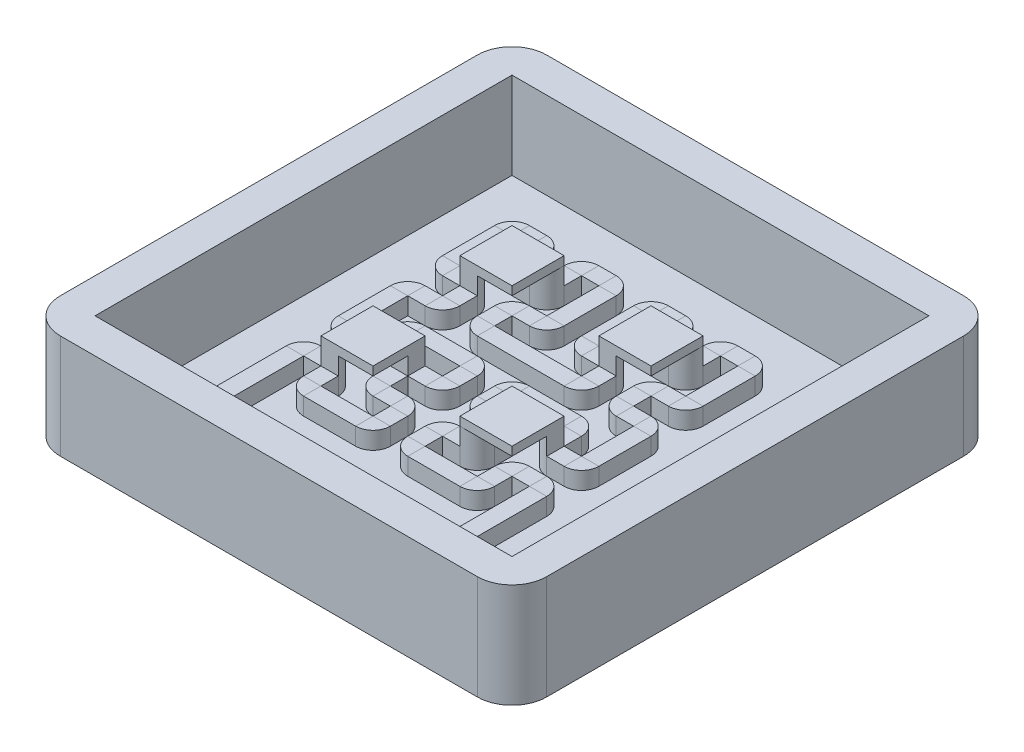
SolidWorks part; units mm, degrees
ref_plane "Front Plane" through (0, 0, 0) normal (0, 0, 1) x (1, 0, 0)
ref_plane "Top Plane" through (0, 0, 0) normal (0, 1, 0) x (1, 0, 0)
ref_plane "Right Plane" through (0, 0, 0) normal (1, 0, 0) x (0, 0, -1)
sketch "Sketch1" plane through (0, 0, 0) normal (0, 1, 0) x (1, 0, 0)
  line L0 (1, 1) -> (3, -1) construction
  line L1 (-1, -1) -> (1, -1)
  line L2 (-1, -1) -> (-1, 1)
  line L3 (-1, 1) -> (1, 1)
  line L4 (1, -1) -> (1, 1)
  line L5 (-1, -1) -> (1, 1) construction
  line L6 (-1, 1) -> (1, -1) construction
  line L7 (1, -1) -> (3, 1) construction
  line L8 (1, 1) -> (3, 1)
  line L9 (3, -1) -> (3, 1)
  line L10 (1, -1) -> (1, 1)
  line L11 (1, -1) -> (3, -1)
  line L12 (3, 1) -> (5, -1) construction
  line L13 (3, -1) -> (5, 1) construction
  line L14 (3, 1) -> (5, 1)
  line L15 (5, -1) -> (5, 1)
  line L16 (3, -1) -> (3, 1)
  line L17 (3, -1) -> (5, -1)
  line L18 (5, 1) -> (7, -1) construction
  line L19 (5, -1) -> (7, 1) construction
  line L20 (5, 1) -> (7, 1)
  line L21 (7, -1) -> (7, 1)
  line L22 (5, -1) -> (5, 1)
  line L23 (5, -1) -> (7, -1)
  line L24 (7, 1) -> (9, -1) construction
  line L25 (7, -1) -> (9, 1) construction
  line L26 (7, 1) -> (9, 1)
  line L27 (9, -1) -> (9, 1)
  line L28 (7, -1) -> (7, 1)
  line L29 (7, -1) -> (9, -1)
  line L30 (9, 1) -> (11, -1) construction
  line L31 (9, -1) -> (11, 1) construction
  line L32 (9, 1) -> (11, 1)
  line L33 (11, -1) -> (11, 1)
  line L34 (9, -1) -> (9, 1)
  line L35 (9, -1) -> (11, -1)
  line L36 (11, 1) -> (13, -1) construction
  line L37 (11, -1) -> (13, 1) construction
  line L38 (11, 1) -> (13, 1)
  line L39 (13, -1) -> (13, 1)
  line L40 (11, -1) -> (11, 1)
  line L41 (11, -1) -> (13, -1)
  line L42 (13, 1) -> (15, -1) construction
  line L43 (13, -1) -> (15, 1) construction
  line L44 (13, 1) -> (15, 1)
  line L45 (15, -1) -> (15, 1)
  line L46 (13, -1) -> (13, 1)
  line L47 (13, -1) -> (15, -1)
  line L96 (-1, 1) -> (1, 1)
  line L97 (-1, 1) -> (-1, 3)
  line L98 (-1, 3) -> (1, 3)
  line L99 (1, 1) -> (1, 3)
  line L100 (1, 3) -> (3, 3)
  line L101 (3, 1) -> (3, 3)
  line L102 (1, 1) -> (1, 3)
  line L103 (1, 1) -> (3, 1)
  line L104 (3, 3) -> (5, 3)
  line L105 (5, 1) -> (5, 3)
  line L106 (3, 1) -> (3, 3)
  line L107 (3, 1) -> (5, 1)
  line L108 (5, 3) -> (7, 3)
  line L109 (7, 1) -> (7, 3)
  line L110 (5, 1) -> (5, 3)
  line L111 (5, 1) -> (7, 1)
  line L112 (7, 3) -> (9, 3)
  line L113 (9, 1) -> (9, 3)
  line L114 (7, 1) -> (7, 3)
  line L115 (7, 1) -> (9, 1)
  line L116 (9, 3) -> (11, 3)
  line L117 (11, 1) -> (11, 3)
  line L118 (9, 1) -> (9, 3)
  line L119 (9, 1) -> (11, 1)
  line L120 (11, 3) -> (13, 3)
  line L121 (13, 1) -> (13, 3)
  line L122 (11, 1) -> (11, 3)
  line L123 (11, 1) -> (13, 1)
  line L124 (13, 3) -> (15, 3)
  line L125 (15, 1) -> (15, 3)
  line L126 (13, 1) -> (13, 3)
  line L127 (13, 1) -> (15, 1)
  line L160 (1, 3) -> (3, 1) construction
  line L161 (-1, 1) -> (1, 3) construction
  line L162 (-1, 3) -> (1, 1) construction
  line L163 (1, 1) -> (3, 3) construction
  line L164 (3, 3) -> (5, 1) construction
  line L165 (3, 1) -> (5, 3) construction
  line L166 (5, 3) -> (7, 1) construction
  line L167 (5, 1) -> (7, 3) construction
  line L168 (7, 3) -> (9, 1) construction
  line L169 (7, 1) -> (9, 3) construction
  line L170 (9, 3) -> (11, 1) construction
  line L171 (9, 1) -> (11, 3) construction
  line L172 (11, 3) -> (13, 1) construction
  line L173 (11, 1) -> (13, 3) construction
  line L174 (13, 3) -> (15, 1) construction
  line L175 (13, 1) -> (15, 3) construction
  line L192 (-1, 3) -> (1, 3)
  line L193 (-1, 3) -> (-1, 5)
  line L194 (-1, 5) -> (1, 5)
  line L195 (1, 3) -> (1, 5)
  line L196 (1, 5) -> (3, 5)
  line L197 (3, 3) -> (3, 5)
  line L198 (1, 3) -> (1, 5)
  line L199 (1, 3) -> (3, 3)
  line L200 (3, 5) -> (5, 5)
  line L201 (5, 3) -> (5, 5)
  line L202 (3, 3) -> (3, 5)
  line L203 (3, 3) -> (5, 3)
  line L204 (5, 5) -> (7, 5)
  line L205 (7, 3) -> (7, 5)
  line L206 (5, 3) -> (5, 5)
  line L207 (5, 3) -> (7, 3)
  line L208 (7, 5) -> (9, 5)
  line L209 (9, 3) -> (9, 5)
  line L210 (7, 3) -> (7, 5)
  line L211 (7, 3) -> (9, 3)
  line L212 (9, 5) -> (11, 5)
  line L213 (11, 3) -> (11, 5)
  line L214 (9, 3) -> (9, 5)
  line L215 (9, 3) -> (11, 3)
  line L216 (11, 5) -> (13, 5)
  line L217 (13, 3) -> (13, 5)
  line L218 (11, 3) -> (11, 5)
  line L219 (11, 3) -> (13, 3)
  line L220 (13, 5) -> (15, 5)
  line L221 (15, 3) -> (15, 5)
  line L222 (13, 3) -> (13, 5)
  line L223 (13, 3) -> (15, 3)
  line L256 (1, 5) -> (3, 3) construction
  line L257 (-1, 3) -> (1, 5) construction
  line L258 (-1, 5) -> (1, 3) construction
  line L259 (1, 3) -> (3, 5) construction
  line L260 (3, 5) -> (5, 3) construction
  line L261 (3, 3) -> (5, 5) construction
  line L262 (5, 5) -> (7, 3) construction
  line L263 (5, 3) -> (7, 5) construction
  line L264 (7, 5) -> (9, 3) construction
  line L265 (7, 3) -> (9, 5) construction
  line L266 (9, 5) -> (11, 3) construction
  line L267 (9, 3) -> (11, 5) construction
  line L268 (11, 5) -> (13, 3) construction
  line L269 (11, 3) -> (13, 5) construction
  line L270 (13, 5) -> (15, 3) construction
  line L271 (13, 3) -> (15, 5) construction
  line L288 (-1, 5) -> (1, 5)
  line L289 (-1, 5) -> (-1, 7)
  line L290 (-1, 7) -> (1, 7)
  line L291 (1, 5) -> (1, 7)
  line L292 (1, 7) -> (3, 7)
  line L293 (3, 5) -> (3, 7)
  line L294 (1, 5) -> (1, 7)
  line L295 (1, 5) -> (3, 5)
  line L296 (3, 7) -> (5, 7)
  line L297 (5, 5) -> (5, 7)
  line L298 (3, 5) -> (3, 7)
  line L299 (3, 5) -> (5, 5)
  line L300 (5, 7) -> (7, 7)
  line L301 (7, 5) -> (7, 7)
  line L302 (5, 5) -> (5, 7)
  line L303 (5, 5) -> (7, 5)
  line L304 (7, 7) -> (9, 7)
  line L305 (9, 5) -> (9, 7)
  line L306 (7, 5) -> (7, 7)
  line L307 (7, 5) -> (9, 5)
  line L308 (9, 7) -> (11, 7)
  line L309 (11, 5) -> (11, 7)
  line L310 (9, 5) -> (9, 7)
  line L311 (9, 5) -> (11, 5)
  line L312 (11, 7) -> (13, 7)
  line L313 (13, 5) -> (13, 7)
  line L314 (11, 5) -> (11, 7)
  line L315 (11, 5) -> (13, 5)
  line L316 (13, 7) -> (15, 7)
  line L317 (15, 5) -> (15, 7)
  line L318 (13, 5) -> (13, 7)
  line L319 (13, 5) -> (15, 5)
  line L352 (1, 7) -> (3, 5) construction
  line L353 (-1, 5) -> (1, 7) construction
  line L354 (-1, 7) -> (1, 5) construction
  line L355 (1, 5) -> (3, 7) construction
  line L356 (3, 7) -> (5, 5) construction
  line L357 (3, 5) -> (5, 7) construction
  line L358 (5, 7) -> (7, 5) construction
  line L359 (5, 5) -> (7, 7) construction
  line L360 (7, 7) -> (9, 5) construction
  line L361 (7, 5) -> (9, 7) construction
  line L362 (9, 7) -> (11, 5) construction
  line L363 (9, 5) -> (11, 7) construction
  line L364 (11, 7) -> (13, 5) construction
  line L365 (11, 5) -> (13, 7) construction
  line L366 (13, 7) -> (15, 5) construction
  line L367 (13, 5) -> (15, 7) construction
  line L384 (-1, 7) -> (1, 7)
  line L385 (-1, 7) -> (-1, 9)
  line L386 (-1, 9) -> (1, 9)
  line L387 (1, 7) -> (1, 9)
  line L388 (1, 9) -> (3, 9)
  line L389 (3, 7) -> (3, 9)
  line L390 (1, 7) -> (1, 9)
  line L391 (1, 7) -> (3, 7)
  line L392 (3, 9) -> (5, 9)
  line L393 (5, 7) -> (5, 9)
  line L394 (3, 7) -> (3, 9)
  line L395 (3, 7) -> (5, 7)
  line L396 (5, 9) -> (7, 9)
  line L397 (7, 7) -> (7, 9)
  line L398 (5, 7) -> (5, 9)
  line L399 (5, 7) -> (7, 7)
  line L400 (7, 9) -> (9, 9)
  line L401 (9, 7) -> (9, 9)
  line L402 (7, 7) -> (7, 9)
  line L403 (7, 7) -> (9, 7)
  line L404 (9, 9) -> (11, 9)
  line L405 (11, 7) -> (11, 9)
  line L406 (9, 7) -> (9, 9)
  line L407 (9, 7) -> (11, 7)
  line L408 (11, 9) -> (13, 9)
  line L409 (13, 7) -> (13, 9)
  line L410 (11, 7) -> (11, 9)
  line L411 (11, 7) -> (13, 7)
  line L412 (13, 9) -> (15, 9)
  line L413 (15, 7) -> (15, 9)
  line L414 (13, 7) -> (13, 9)
  line L415 (13, 7) -> (15, 7)
  line L448 (1, 9) -> (3, 7) construction
  line L449 (-1, 7) -> (1, 9) construction
  line L450 (-1, 9) -> (1, 7) construction
  line L451 (1, 7) -> (3, 9) construction
  line L452 (3, 9) -> (5, 7) construction
  line L453 (3, 7) -> (5, 9) construction
  line L454 (5, 9) -> (7, 7) construction
  line L455 (5, 7) -> (7, 9) construction
  line L456 (7, 9) -> (9, 7) construction
  line L457 (7, 7) -> (9, 9) construction
  line L458 (9, 9) -> (11, 7) construction
  line L459 (9, 7) -> (11, 9) construction
  line L460 (11, 9) -> (13, 7) construction
  line L461 (11, 7) -> (13, 9) construction
  line L462 (13, 9) -> (15, 7) construction
  line L463 (13, 7) -> (15, 9) construction
  line L480 (-1, 9) -> (1, 9)
  line L481 (-1, 9) -> (-1, 11)
  line L482 (-1, 11) -> (1, 11)
  line L483 (1, 9) -> (1, 11)
  line L484 (1, 11) -> (3, 11)
  line L485 (3, 9) -> (3, 11)
  line L486 (1, 9) -> (1, 11)
  line L487 (1, 9) -> (3, 9)
  line L488 (3, 11) -> (5, 11)
  line L489 (5, 9) -> (5, 11)
  line L490 (3, 9) -> (3, 11)
  line L491 (3, 9) -> (5, 9)
  line L492 (5, 11) -> (7, 11)
  line L493 (7, 9) -> (7, 11)
  line L494 (5, 9) -> (5, 11)
  line L495 (5, 9) -> (7, 9)
  line L496 (7, 11) -> (9, 11)
  line L497 (9, 9) -> (9, 11)
  line L498 (7, 9) -> (7, 11)
  line L499 (7, 9) -> (9, 9)
  line L500 (9, 11) -> (11, 11)
  line L501 (11, 9) -> (11, 11)
  line L502 (9, 9) -> (9, 11)
  line L503 (9, 9) -> (11, 9)
  line L504 (11, 11) -> (13, 11)
  line L505 (13, 9) -> (13, 11)
  line L506 (11, 9) -> (11, 11)
  line L507 (11, 9) -> (13, 9)
  line L508 (13, 11) -> (15, 11)
  line L509 (15, 9) -> (15, 11)
  line L510 (13, 9) -> (13, 11)
  line L511 (13, 9) -> (15, 9)
  line L544 (1, 11) -> (3, 9) construction
  line L545 (-1, 9) -> (1, 11) construction
  line L546 (-1, 11) -> (1, 9) construction
  line L547 (1, 9) -> (3, 11) construction
  line L548 (3, 11) -> (5, 9) construction
  line L549 (3, 9) -> (5, 11) construction
  line L550 (5, 11) -> (7, 9) construction
  line L551 (5, 9) -> (7, 11) construction
  line L552 (7, 11) -> (9, 9) construction
  line L553 (7, 9) -> (9, 11) construction
  line L554 (9, 11) -> (11, 9) construction
  line L555 (9, 9) -> (11, 11) construction
  line L556 (11, 11) -> (13, 9) construction
  line L557 (11, 9) -> (13, 11) construction
  line L558 (13, 11) -> (15, 9) construction
  line L559 (13, 9) -> (15, 11) construction
  line L576 (-1, 11) -> (1, 11)
  line L577 (-1, 11) -> (-1, 13)
  line L578 (-1, 13) -> (1, 13)
  line L579 (1, 11) -> (1, 13)
  line L580 (1, 13) -> (3, 13)
  line L581 (3, 11) -> (3, 13)
  line L582 (1, 11) -> (1, 13)
  line L583 (1, 11) -> (3, 11)
  line L584 (3, 13) -> (5, 13)
  line L585 (5, 11) -> (5, 13)
  line L586 (3, 11) -> (3, 13)
  line L587 (3, 11) -> (5, 11)
  line L588 (5, 13) -> (7, 13)
  line L589 (7, 11) -> (7, 13)
  line L590 (5, 11) -> (5, 13)
  line L591 (5, 11) -> (7, 11)
  line L592 (7, 13) -> (9, 13)
  line L593 (9, 11) -> (9, 13)
  line L594 (7, 11) -> (7, 13)
  line L595 (7, 11) -> (9, 11)
  line L596 (9, 13) -> (11, 13)
  line L597 (11, 11) -> (11, 13)
  line L598 (9, 11) -> (9, 13)
  line L599 (9, 11) -> (11, 11)
  line L600 (11, 13) -> (13, 13)
  line L601 (13, 11) -> (13, 13)
  line L602 (11, 11) -> (11, 13)
  line L603 (11, 11) -> (13, 11)
  line L604 (13, 13) -> (15, 13)
  line L605 (15, 11) -> (15, 13)
  line L606 (13, 11) -> (13, 13)
  line L607 (13, 11) -> (15, 11)
  line L640 (1, 13) -> (3, 11) construction
  line L641 (-1, 11) -> (1, 13) construction
  line L642 (-1, 13) -> (1, 11) construction
  line L643 (1, 11) -> (3, 13) construction
  line L644 (3, 13) -> (5, 11) construction
  line L645 (3, 11) -> (5, 13) construction
  line L646 (5, 13) -> (7, 11) construction
  line L647 (5, 11) -> (7, 13) construction
  line L648 (7, 13) -> (9, 11) construction
  line L649 (7, 11) -> (9, 13) construction
  line L650 (9, 13) -> (11, 11) construction
  line L651 (9, 11) -> (11, 13) construction
  line L652 (11, 13) -> (13, 11) construction
  line L653 (11, 11) -> (13, 13) construction
  line L654 (13, 13) -> (15, 11) construction
  line L655 (13, 11) -> (15, 13) construction
  line L672 (-1, 13) -> (1, 13)
  line L673 (-1, 13) -> (-1, 15)
  line L674 (-1, 15) -> (1, 15)
  line L675 (1, 13) -> (1, 15)
  line L676 (1, 15) -> (3, 15)
  line L677 (3, 13) -> (3, 15)
  line L678 (1, 13) -> (1, 15)
  line L679 (1, 13) -> (3, 13)
  line L680 (3, 15) -> (5, 15)
  line L681 (5, 13) -> (5, 15)
  line L682 (3, 13) -> (3, 15)
  line L683 (3, 13) -> (5, 13)
  line L684 (5, 15) -> (7, 15)
  line L685 (7, 13) -> (7, 15)
  line L686 (5, 13) -> (5, 15)
  line L687 (5, 13) -> (7, 13)
  line L688 (7, 15) -> (9, 15)
  line L689 (9, 13) -> (9, 15)
  line L690 (7, 13) -> (7, 15)
  line L691 (7, 13) -> (9, 13)
  line L692 (9, 15) -> (11, 15)
  line L693 (11, 13) -> (11, 15)
  line L694 (9, 13) -> (9, 15)
  line L695 (9, 13) -> (11, 13)
  line L696 (11, 15) -> (13, 15)
  line L697 (13, 13) -> (13, 15)
  line L698 (11, 13) -> (11, 15)
  line L699 (11, 13) -> (13, 13)
  line L700 (13, 15) -> (15, 15)
  line L701 (15, 13) -> (15, 15)
  line L702 (13, 13) -> (13, 15)
  line L703 (13, 13) -> (15, 13)
  line L736 (1, 15) -> (3, 13) construction
  line L737 (-1, 13) -> (1, 15) construction
  line L738 (-1, 15) -> (1, 13) construction
  line L739 (1, 13) -> (3, 15) construction
  line L740 (3, 15) -> (5, 13) construction
  line L741 (3, 13) -> (5, 15) construction
  line L742 (5, 15) -> (7, 13) construction
  line L743 (5, 13) -> (7, 15) construction
  line L744 (7, 15) -> (9, 13) construction
  line L745 (7, 13) -> (9, 15) construction
  line L746 (9, 15) -> (11, 13) construction
  line L747 (9, 13) -> (11, 15) construction
  line L748 (11, 15) -> (13, 13) construction
  line L749 (11, 13) -> (13, 15) construction
  line L750 (13, 15) -> (15, 13) construction
  line L751 (13, 13) -> (15, 15) construction
  point P0 (0, 0)
  point P7 (2, 0)
  point P69 (0, 2)
  point P134 (0, 4)
  point P199 (0, 6)
  point P264 (0, 8)
  point P329 (0, 10)
  point P394 (0, 12)
  point P459 (0, 14)
  dimension "D1" = 2
  dimension "D3" = 2
  dimension "D5" = 2
  dimension "D2" = 8
  dimension "D4" = 8
sketch "Sketch2" plane through (0, 0, 0) normal (0, 1, 0) x (1, 0, 0)
  line L0 (0, 0) -> (0, 1.5)
  line L1 (0.5, 2) -> (1.5, 2)
  line L2 (0, 0) -> (0, 14) construction
  line L3 (1, 3) -> (3, 1) construction
  line L4 (2, 1.5) -> (2, 0.5)
  line L6 (1, 1) -> (3, -1) construction
  line L7 (2.5, 0) -> (5.5, 0)
  line L8 (5, 1) -> (7, -1) construction
  line L9 (6, 0.5) -> (6, 1.5)
  line L10 (5, 1) -> (7, 3) construction
  line L11 (5.5, 2) -> (4.5, 2)
  line L13 (3, 3) -> (5, 1) construction
  line L14 (4, 2.5) -> (4, 3.5)
  line L15 (3, 5) -> (5, 3) construction
  line L17 (4.5, 4) -> (5.5, 4)
  line L18 (5, 5) -> (7, 3) construction
  line L19 (6, 4.5) -> (6, 5.5)
  line L21 (5, 7) -> (7, 5) construction
  line L22 (5.5, 6) -> (2.5, 6)
  line L23 (1, 7) -> (3, 5) construction
  line L25 (2, 5.5) -> (2, 4.5)
  line L26 (1, 5) -> (3, 3) construction
  line L27 (1.5, 4) -> (0.5, 4)
  line L29 (0, 4.5) -> (0, 7.5)
  line L30 (0.5, 8) -> (1.5, 8)
  line L31 (1, 9) -> (3, 7) construction
  line L33 (2, 8.5) -> (2, 9.5)
  line L34 (1, 11) -> (3, 9) construction
  line L35 (1.5, 10) -> (0.5, 10)
  line L37 (0, 10.5) -> (0, 13.5)
  line L38 (0.5, 14) -> (1.5, 14)
  line L39 (1, 15) -> (3, 13) construction
  line L41 (2, 13.5) -> (2, 12.5)
  line L42 (1, 13) -> (3, 11) construction
  line L43 (2.5, 12) -> (3.5, 12)
  line L45 (3, 13) -> (5, 11) construction
  line L46 (4, 12.5) -> (4, 13.5)
  line L47 (3, 15) -> (5, 13) construction
  line L49 (4.5, 14) -> (5.5, 14)
  line L50 (5, 13) -> (7, 15) construction
  line L51 (6, 13.5) -> (6, 10.5)
  line L53 (5, 11) -> (7, 9) construction
  line L54 (5.5, 10) -> (4.5, 10)
  line L55 (3, 11) -> (5, 9) construction
  line L57 (4, 9.5) -> (4, 8.5)
  line L58 (3, 9) -> (5, 7) construction
  line L59 (4.5, 8) -> (9.5, 8)
  line L61 (9, 7) -> (11, 9) construction
  line L62 (10, 8.5) -> (10, 9.5)
  line L63 (9, 9) -> (11, 11) construction
  line L65 (9.5, 10) -> (8.5, 10)
  line L66 (7, 11) -> (9, 9) construction
  line L67 (8, 10.5) -> (8, 13.5)
  line L69 (7, 15) -> (9, 13) construction
  line L70 (8.5, 14) -> (9.5, 14)
  line L71 (9, 15) -> (11, 13) construction
  line L73 (10, 13.5) -> (10, 12.5)
  line L74 (9, 11) -> (11, 13) construction
  line L75 (10.5, 12) -> (11.5, 12)
  line L77 (11, 13) -> (13, 11) construction
  line L78 (12, 12.5) -> (12, 13.5)
  line L79 (11, 15) -> (13, 13) construction
  line L81 (12.5, 14) -> (13.5, 14)
  line L82 (13, 15) -> (15, 13) construction
  line L83 (14, 13.5) -> (14, 10.5)
  line L85 (13, 11) -> (15, 9) construction
  line L86 (13.5, 10) -> (12.5, 10)
  line L87 (11, 11) -> (13, 9) construction
  line L89 (12, 9.5) -> (12, 8.5)
  line L90 (11, 9) -> (13, 7) construction
  line L92 (12.5, 8) -> (13.5, 8)
  line L93 (13, 9) -> (15, 7) construction
  line L94 (14, 7.5) -> (14, 4.5)
  line L96 (13, 5) -> (15, 3) construction
  line L97 (13.5, 4) -> (12.5, 4)
  line L99 (11, 5) -> (13, 3) construction
  line L100 (12, 4.5) -> (12, 5.5)
  line L102 (11, 7) -> (13, 5) construction
  line L103 (11.5, 6) -> (8.5, 6)
  line L104 (7, 7) -> (9, 5) construction
  line L106 (8, 5.5) -> (8, 4.5)
  line L107 (7, 5) -> (9, 3) construction
  line L108 (8.5, 4) -> (9.5, 4)
  line L110 (9, 5) -> (11, 3) construction
  line L111 (10, 3.5) -> (10, 2.5)
  line L112 (9, 3) -> (11, 1) construction
  line L114 (9.5, 2) -> (8.5, 2)
  line L115 (7, 3) -> (9, 1) construction
  line L116 (8, 1.5) -> (8, 0.5)
  line L118 (7, 1) -> (9, -1) construction
  line L119 (8.5, 0) -> (11.5, 0)
  line L121 (11, 1) -> (13, -1) construction
  line L122 (12, 0.5) -> (12, 1.5)
  line L124 (11, 3) -> (13, 1) construction
  line L125 (12.5, 2) -> (13.5, 2)
  line L127 (13, 1) -> (15, 3) construction
  line L128 (14, 1.5) -> (14, 0)
  line L130 (13, 1) -> (15, -1) construction
  arc A0 (14, 1.5) -> (13.5, 2) centre (13.5, 1.5) ccw
  arc A1 (12.5, 2) -> (12, 1.5) centre (12.5, 1.5) ccw
  arc A2 (12, 0.5) -> (11.5, 0) centre (11.5, 0.5) cw
  arc A3 (8.5, 0) -> (8, 0.5) centre (8.5, 0.5) cw
  arc A4 (8, 1.5) -> (8.5, 2) centre (8.5, 1.5) cw
  arc A5 (9.5, 2) -> (10, 2.5) centre (9.5, 2.5) ccw
  arc A6 (10, 3.5) -> (9.5, 4) centre (9.5, 3.5) ccw
  arc A7 (8.5, 4) -> (8, 4.5) centre (8.5, 4.5) cw
  arc A8 (8, 5.5) -> (8.5, 6) centre (8.5, 5.5) cw
  arc A9 (11.5, 6) -> (12, 5.5) centre (11.5, 5.5) cw
  arc A10 (12, 4.5) -> (12.5, 4) centre (12.5, 4.5) ccw
  arc A11 (13.5, 4) -> (14, 4.5) centre (13.5, 4.5) ccw
  arc A12 (14, 7.5) -> (13.5, 8) centre (13.5, 7.5) ccw
  arc A13 (12.5, 8) -> (12, 8.5) centre (12.5, 8.5) cw
  arc A14 (12, 9.5) -> (12.5, 10) centre (12.5, 9.5) cw
  arc A15 (13.5, 10) -> (14, 10.5) centre (13.5, 10.5) ccw
  arc A16 (14, 13.5) -> (13.5, 14) centre (13.5, 13.5) ccw
  arc A17 (12.5, 14) -> (12, 13.5) centre (12.5, 13.5) ccw
  arc A18 (12, 12.5) -> (11.5, 12) centre (11.5, 12.5) cw
  arc A19 (10.5, 12) -> (10, 12.5) centre (10.5, 12.5) cw
  arc A20 (10, 13.5) -> (9.5, 14) centre (9.5, 13.5) ccw
  arc A21 (8.5, 14) -> (8, 13.5) centre (8.5, 13.5) ccw
  arc A22 (8, 10.5) -> (8.5, 10) centre (8.5, 10.5) ccw
  arc A23 (9.5, 10) -> (10, 9.5) centre (9.5, 9.5) cw
  arc A24 (10, 8.5) -> (9.5, 8) centre (9.5, 8.5) cw
  arc A25 (4.5, 8) -> (4, 8.5) centre (4.5, 8.5) cw
  arc A26 (4, 9.5) -> (4.5, 10) centre (4.5, 9.5) cw
  arc A27 (5.5, 10) -> (6, 10.5) centre (5.5, 10.5) ccw
  arc A28 (6, 13.5) -> (5.5, 14) centre (5.5, 13.5) ccw
  arc A29 (4.5, 14) -> (4, 13.5) centre (4.5, 13.5) ccw
  arc A30 (4, 12.5) -> (3.5, 12) centre (3.5, 12.5) cw
  arc A31 (2.5, 12) -> (2, 12.5) centre (2.5, 12.5) cw
  arc A32 (2, 13.5) -> (1.5, 14) centre (1.5, 13.5) ccw
  arc A33 (0.5, 14) -> (0, 13.5) centre (0.5, 13.5) ccw
  arc A34 (0, 10.5) -> (0.5, 10) centre (0.5, 10.5) ccw
  arc A35 (1.5, 10) -> (2, 9.5) centre (1.5, 9.5) cw
  arc A36 (2, 8.5) -> (1.5, 8) centre (1.5, 8.5) cw
  arc A37 (0.5, 8) -> (0, 7.5) centre (0.5, 7.5) ccw
  arc A38 (0, 4.5) -> (0.5, 4) centre (0.5, 4.5) ccw
  arc A39 (2, 4.5) -> (1.5, 4) centre (1.5, 4.5) cw
  arc A40 (2, 5.5) -> (2.5, 6) centre (2.5, 5.5) cw
  arc A41 (5.5, 6) -> (6, 5.5) centre (5.5, 5.5) cw
  arc A42 (6, 4.5) -> (5.5, 4) centre (5.5, 4.5) cw
  arc A43 (4.5, 4) -> (4, 3.5) centre (4.5, 3.5) ccw
  arc A44 (4, 2.5) -> (4.5, 2) centre (4.5, 2.5) ccw
  arc A45 (5.5, 2) -> (6, 1.5) centre (5.5, 1.5) cw
  arc A46 (6, 0.5) -> (5.5, 0) centre (5.5, 0.5) cw
  arc A47 (2.5, 0) -> (2, 0.5) centre (2.5, 0.5) cw
  arc A48 (2, 1.5) -> (1.5, 2) centre (1.5, 1.5) ccw
  arc A49 (0.5, 2) -> (0, 1.5) centre (0.5, 1.5) ccw
  point P146 (14, 2)
  point P149 (12, 2)
  point P152 (12, 0)
  point P155 (8, 0)
  point P158 (8, 2)
  point P161 (10, 2)
  point P164 (10, 4)
  point P167 (8, 4)
  point P170 (8, 6)
  point P173 (12, 6)
  point P176 (12, 4)
  point P179 (14, 4)
  point P182 (14, 8)
  point P185 (12, 8)
  point P188 (12, 10)
  point P191 (14, 10)
  point P194 (14, 14)
  point P197 (12, 14)
  point P200 (12, 12)
  point P203 (10, 12)
  point P206 (10, 14)
  point P209 (8, 14)
  point P212 (8, 10)
  point P215 (10, 10)
  point P218 (10, 8)
  point P221 (4, 8)
  point P224 (4, 10)
  point P227 (6, 10)
  point P230 (6, 14)
  point P233 (4, 14)
  point P236 (4, 12)
  point P239 (2, 12)
  point P242 (2, 14)
  point P245 (0, 14)
  point P248 (0, 10)
  point P251 (2, 10)
  point P254 (2, 8)
  point P257 (0, 8)
  point P260 (0, 4)
  point P263 (2, 4)
  point P266 (2, 6)
  point P269 (6, 6)
  point P272 (6, 4)
  point P275 (4, 4)
  point P278 (4, 2)
  point P281 (6, 2)
  point P284 (6, 0)
  point P287 (2, 0)
  point P290 (2, 2)
  point P293 (0, 2)
  dimension "D1" = 0.5
ref_plane "Plane1" through (0, 0, 0) normal (0, 0, 1) x (1, 0, 0)
sketch "Sketch3" plane through (0, 0, 0) normal (0, 0, 1) x (1, 0, 0)
  line L6 (-0.5, -0.5) -> (0.5, -0.5)
  line L7 (-0.5, -0.5) -> (-0.5, 0.5)
  line L8 (-0.5, 0.5) -> (0.5, 0.5)
  line L9 (0.5, -0.5) -> (0.5, 0.5)
  line L10 (-0.5, -0.5) -> (0.5, 0.5) construction
  line L11 (-0.5, 0.5) -> (0.5, -0.5) construction
  point P1 (0, 0)
  dimension "D2" = 1
sweep "Sweep1" add profiles "Sketch3" path "Sketch2"
sketch "Sketch4" plane through (0, 0, 0) normal (0, 0, 1) x (1, 0, 0)
  line L1 (-0.5, -0.5) -> (0.5, -0.5)
  line L2 (-0.5, -0.5) -> (-0.5, 0.5)
  line L3 (-0.5, 0.5) -> (0.5, 0.5)
  line L4 (0.5, -0.5) -> (0.5, 0.5)
  line L5 (-0.5, -0.5) -> (0.5, 0.5) construction
  line L6 (-0.5, 0.5) -> (0.5, -0.5) construction
  line L7 (13.5, 0.5) -> (14.5, 0.5)
  line L8 (13.5, 0.5) -> (13.5, -0.5)
  line L9 (13.5, -0.5) -> (14.5, -0.5)
  line L10 (14.5, 0.5) -> (14.5, -0.5)
  point P0 (0, 0)
extrude "Boss-Extrude1" add sketch "Sketch4" along normal blind 5
ref_plane "Plane2" through (0, -2, 0) normal (0, 1, 0) x (1, 0, 0)
sketch "Sketch7" plane through (0, -2, 0) normal (0, 1, 0) x (1, 0, 0)
  line L0 (5.5, 14.5) -> (5.5, -0.5) construction
  line L6 (14.5, -5) -> (13.5, -5) construction
  line L7 (-5, -5) -> (19, -5)
  line L8 (5.5, -0.5) -> (8.5, -0.5) construction
  line L9 (-5, -5) -> (-5, 19)
  line L10 (-5, 19) -> (19, 19)
  line L11 (8.5, -0.5) -> (8.5, 14.5) construction
  line L12 (8.5, 7) -> (5.5, 7) construction
  line L18 (2.5, -0.5) -> (5.5, -0.5) construction
  line L19 (5.5, -0.5) -> (5.5, 0.5) construction
  line L20 (19, -5) -> (19, 19)
  line L21 (-5, -5) -> (19, 19) construction
  line L22 (-5, 19) -> (19, -5) construction
  point P7 (7, 7)
  point P10 (7, 7)
extrude "Boss-Extrude4" add sketch "Sketch7" against normal blind 1 separate body
sketch "Sketch8" plane through (0, -3, 0) normal (0, -1, 0) x (1, 0, 0)
  line L0 (-5, -19) -> (-5, 5) construction
  line L1 (-7, 7) -> (21, 7)
  line L2 (-7, 7) -> (-7, -21)
  line L3 (-7, -21) -> (21, -21)
  line L4 (21, 7) -> (21, -21)
  line L5 (19, 5) -> (19, -19) construction
  line L8 (-5, 5) -> (19, 5)
  line L9 (-5, 5) -> (-5, -19)
  line L10 (-5, -19) -> (19, -19)
  line L11 (19, 5) -> (19, -19)
  dimension "D1" = 2
  dimension "D2" = 2
  dimension "D3" = 2
extrude "Boss-Extrude5" add sketch "Sketch8" against normal blind 5
fillet "Fillet1" radius 2 4 edges at (-7, -0.5, 7) (21, -0.5, 7) (21, -0.5, -21) (-7, -0.5, -21)
sketch "Sketch10" plane through (0, 0, -14.5) normal (0, 0, -1) x (-1, 0, 0)
  line L0 (-1, 0.5) -> (-1, -0.5) construction
  line L1 (-0.5, 0.5) -> (-1.5, 0.5) construction
  line L2 (-0.5, -0.5) -> (-1.5, -0.5) construction
  line L3 (-13, 0.5) -> (-13, -0.5) construction
  line L4 (-12.5, 0.5) -> (-13.5, 0.5) construction
  line L5 (-12.5, -0.5) -> (-13.5, -0.5) construction
  circle A0 centre (-13, 0) radius 0.35
  circle A1 centre (-1, 0) radius 0.35
  dimension "D1" = 0.7
  dimension "D2" = 0.7
extrude "Boss-Extrude7" [suppressed] add sketch "Sketch10" along normal up to surface (4.5 mm away)
sketch "Sketch17" plane through (0, 0.5, 0) normal (0, 1, 0) x (1, 0, 0)
  line L0 (1.5, 9.5) -> (1.5, 10.5)
  line L1 (1.5, 10.5) -> (1.5, 9.5)
  line L2 (1.5, 9.5) -> (2.5, 9.5)
  line L3 (2.5, 8.5) -> (2.5, 9.5) construction
  line L4 (1.5, 9.5) -> (2.5, 9.5)
  line L5 (3.5, 12.5) -> (4.5, 12.5)
  line L6 (3.5, 12.5) -> (3.5, 11.5)
  line L7 (1.5, 1.5) -> (1.5, 2.5)
  line L8 (1.5, 1.5) -> (2.5, 1.5)
  line L9 (3.5, 3.5) -> (4.5, 3.5)
  line L10 (4.5, 3.5) -> (4.5, 4.5)
  line L11 (9.5, 10.5) -> (9.5, 9.5)
  line L12 (9.5, 9.5) -> (10.5, 9.5)
  line L13 (10.5, 9.5) -> (9.5, 9.5) construction
  line L14 (11.5, 11.5) -> (11.5, 12.5)
  line L15 (11.5, 11.5) -> (11.5, 12.5) construction
  line L16 (11.5, 12.5) -> (12.5, 12.5)
  line L17 (11.5, 4.5) -> (12.5, 4.5)
  line L18 (12.5, 4.5) -> (12.5, 3.5)
  line L19 (10.5, 2.5) -> (9.5, 2.5)
  line L20 (9.5, 2.5) -> (9.5, 1.5)
  line L21 (9.5, 1.5) -> (8.5, 1.5) construction
  arc A0 (1.5, 10.5) -> (2.5, 9.5) centre (1.5, 9.5) cw
  arc A1 (4.5, 12.5) -> (3.5, 11.5) centre (3.5, 12.5) cw
  arc A2 (1.5, 2.5) -> (2.5, 1.5) centre (1.5, 1.5) cw
  arc A3 (2.5, 1.5) -> (1.5, 2.5) centre (1.5, 1.5) ccw construction
  arc A4 (3.5, 3.5) -> (4.5, 4.5) centre (4.5, 3.5) cw
  arc A5 (10.5, 9.5) -> (9.5, 10.5) centre (9.5, 9.5) ccw construction
  arc A6 (9.5, 10.5) -> (10.5, 9.5) centre (9.5, 9.5) cw
  arc A7 (11.5, 11.5) -> (12.5, 12.5) centre (11.5, 12.5) ccw construction
  arc A8 (12.5, 12.5) -> (11.5, 11.5) centre (11.5, 12.5) cw
  arc A9 (11.5, 4.5) -> (12.5, 3.5) centre (12.5, 4.5) ccw
  arc A10 (11.5, 4.5) -> (12.5, 3.5) centre (12.5, 4.5) ccw construction
  arc A11 (10.5, 2.5) -> (9.5, 1.5) centre (9.5, 2.5) cw
  arc A12 (1.5, 10.5) -> (2.5, 9.5) centre (1.5, 9.5) cw
extrude "Boss-Extrude11" add sketch "Sketch17" along normal blind 1 contours A4 L9 L10 | A2 L7 L8 | A1 L5 L6 | A6 L11 L12 | A8 L16 L14 | L17 A9 L18 | A11 L19 L20
sketch "Sketch16" plane through (0, 2, 0) normal (0, 1, 0) x (1, 0, 0)
  line L1 (-5, 19) -> (19, 19)
  line L2 (-5, 19) -> (-5, -5)
  line L3 (-5, -5) -> (19, -5)
  line L4 (-7, 19) -> (-7, -5)
  line L5 (-5, -7) -> (19, -7)
  line L6 (21, -5) -> (21, 19)
  line L7 (19, 21) -> (-5, 21)
  line L8 (-7, 19) -> (-7, -5)
  line L9 (-5, -7) -> (19, -7)
  line L10 (21, -5) -> (21, 19)
  line L11 (19, 21) -> (-5, 21)
  line L12 (19, 19) -> (19, -5)
  arc A4 (-7, -5) -> (-5, -7) centre (-5, -5) ccw
  arc A5 (19, -7) -> (21, -5) centre (19, -5) ccw
  arc A6 (21, 19) -> (19, 21) centre (19, 19) ccw
  arc A7 (-5, 21) -> (-7, 19) centre (-5, 19) ccw
  arc A8 (-7, -5) -> (-5, -7) centre (-5, -5) ccw
  arc A9 (19, -7) -> (21, -5) centre (19, -5) ccw
  arc A10 (21, 19) -> (19, 21) centre (19, 19) ccw
  arc A11 (-5, 21) -> (-7, 19) centre (-5, 19) ccw
  dimension "D1" = 0
extrude "Boss-Extrude10" add sketch "Sketch16" along normal blind 1
sketch "Sketch18" plane through (0, 1.5, 0) normal (0, 1, 0) x (1, 0, 0)
  line L1 (9.5, 9.5) -> (12.5, 9.5)
  line L2 (9.5, 9.5) -> (9.5, 12.5)
  line L3 (9.5, 12.5) -> (12.5, 12.5)
  line L4 (12.5, 9.5) -> (12.5, 12.5)
  line L5 (1.5, 9.5) -> (4.5, 9.5)
  line L6 (1.5, 9.5) -> (1.5, 12.5)
  line L7 (1.5, 12.5) -> (4.5, 12.5)
  line L8 (4.5, 9.5) -> (4.5, 12.5)
  line L13 (1.5, 1.5) -> (4.5, 1.5)
  line L14 (1.5, 1.5) -> (1.5, 4.5)
  line L15 (1.5, 4.5) -> (4.5, 4.5)
  line L16 (4.5, 1.5) -> (4.5, 4.5)
  line L17 (9.5, 1.5) -> (12.5, 1.5)
  line L18 (9.5, 1.5) -> (9.5, 4.5)
  line L19 (9.5, 4.5) -> (12.5, 4.5)
  line L20 (12.5, 1.5) -> (12.5, 4.5)
  arc A0 (4.5, 4.5) -> (3.5, 3.5) centre (4.5, 3.5) ccw construction
extrude "Boss-Extrude12" add sketch "Sketch18" along normal blind 0.5
equation "\"length\"= 15"
equation "\"order\"= 8"
equation "\"D2@Sketch1\"=\"order\""
equation "\"width\"= 0.9"
equation "\"th\"= 5"
equation "\"D1\"=  ( \"th\" / 2 )  +  ( \"width\" / 2 )  + 2"
equation "\"D4@Sketch1\"= \"order\""
